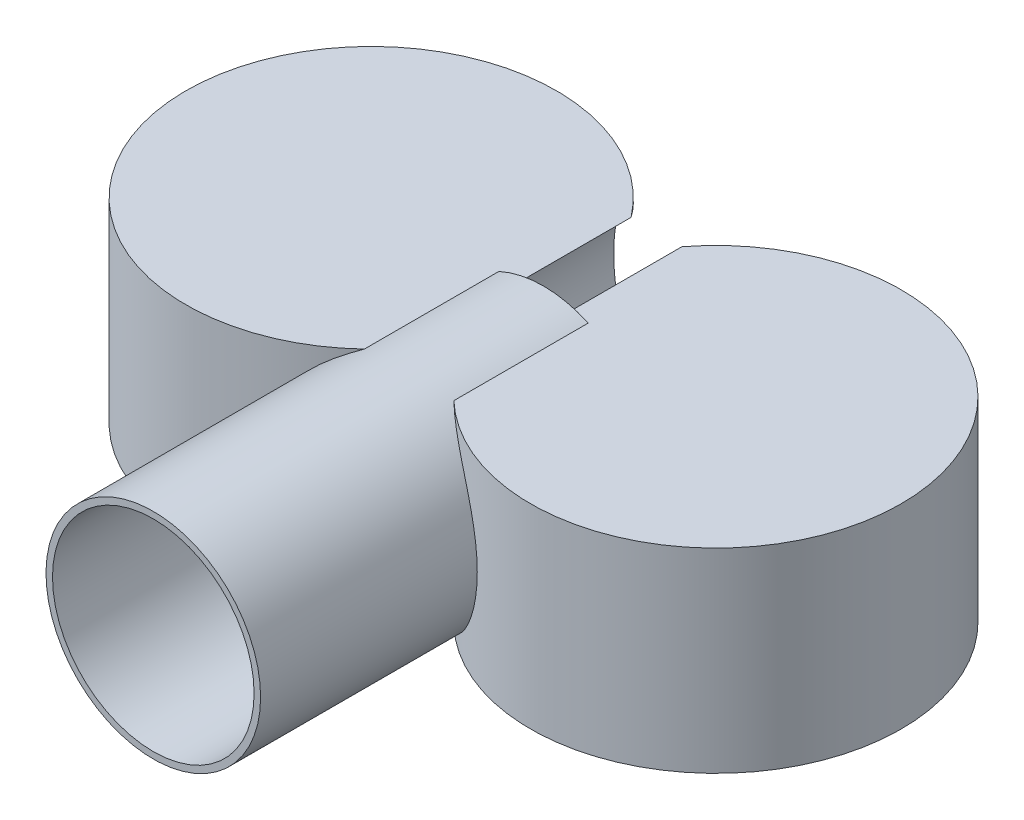
SolidWorks part; units mm, degrees
ref_plane "Front Plane" through (0, 0, 0) normal (0, 0, 1) x (1, 0, 0)
ref_plane "Top Plane" through (0, 0, 0) normal (0, 1, 0) x (1, 0, 0)
ref_plane "Right Plane" through (0, 0, 0) normal (1, 0, 0) x (0, 0, -1)
sketch "Sketch1" plane through (0, 0, 0) normal (0, 1, 0) x (1, 0, 0)
  arc A0 (-16.0193, 10.4881) -> (-16.0193, -10.4881) centre (-42.5193, 0) ccw
  arc A1 (-16.0193, -10.4881) -> (-16.0193, 10.4881) centre (10.4807, 0) ccw
  dimension "D1" = 57
  dimension "D2" = 53
extrude "Boss-Extrude1" add sketch "Sketch1" along normal blind 30
sketch "Sketch2" plane through (0, 0, 0) normal (0, 0, 1) x (1, 0, 0)
  line L0 (-16.0193, 30) -> (-16.0193, 0) construction
  circle A0 centre (-16.0193, 15) radius 16.5
  dimension "D1" = 33
extrude "Boss-Extrude2" add sketch "Sketch2" along normal blind 60
sketch "Sketch3" plane through (0, 0, 60) normal (0, 0, 1) x (1, 0, 0)
  circle A0 centre (-16.0193, 15) radius 15.5
  dimension "D1" = 31
extrude "Cut-Extrude1" cut sketch "Sketch3" against normal through all
